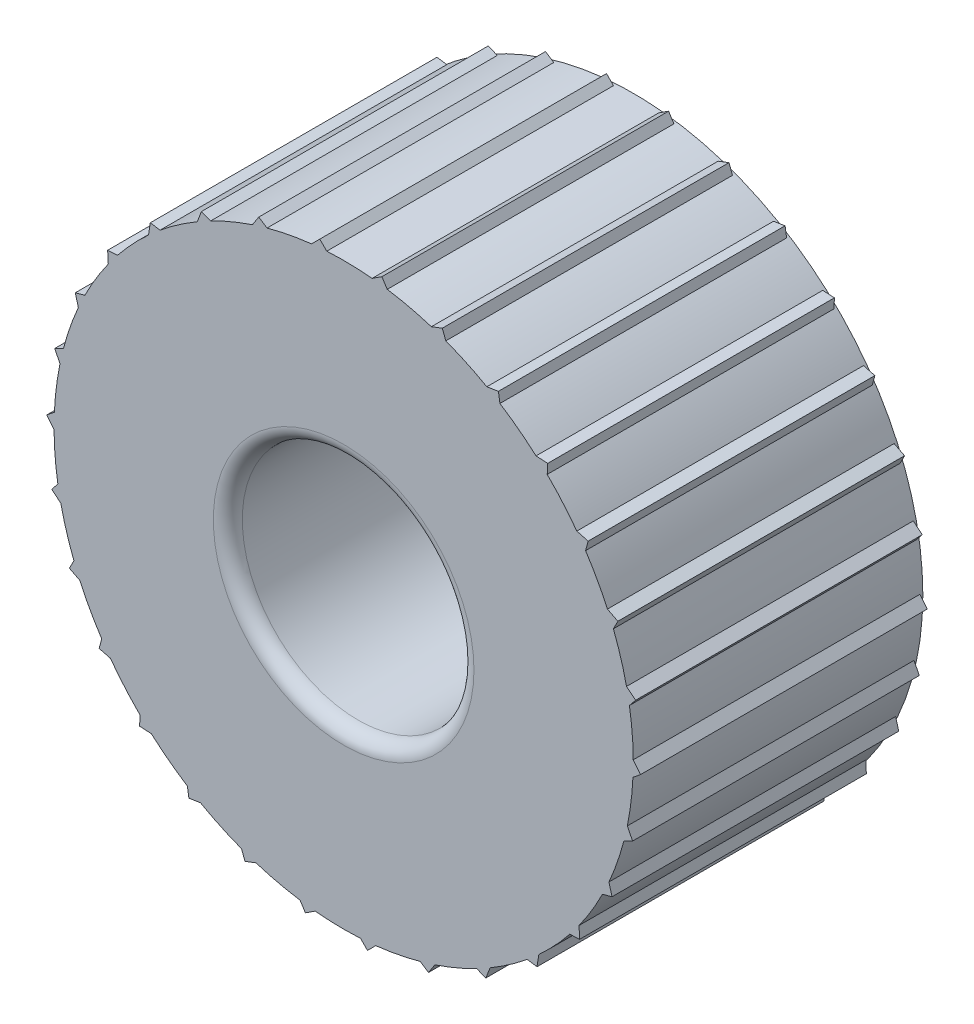
SolidWorks part; units mm, degrees
ref_plane "Front Plane" through (0, 0, 0) normal (0, 0, 1) x (1, 0, 0)
ref_plane "Top Plane" through (0, 0, 0) normal (0, 1, 0) x (1, 0, 0)
ref_plane "Right Plane" through (0, 0, 0) normal (1, 0, 0) x (0, 0, -1)
sketch "Sketch2" plane through (0, 0, 0) normal (0, 0, 1) x (1, 0, 0)
  circle A0 centre (0, 0) radius 100
  circle A1 centre (0, 0) radius 40
  circle A2 centre (0, 0) radius 50
  dimension "D1" = 200
  dimension "D2" = 80
  dimension "D3" = 100
extrude "Boss-Extrude2" add sketch "Sketch2" against normal blind 100 contours A0 A2
sketch "Sketch3" plane through (0, 0, 0) normal (0, 0, 1) x (1, 0, 0)
  circle A0 centre (0, 0) radius 50
extrude "Boss-Extrude3" add sketch "Sketch3" against normal blind 100
sketch "Sketch4" plane through (0, 0, 0) normal (0, 0, 1) x (1, 0, 0)
  circle A0 centre (0, 0) radius 40
  dimension "D1" = 80
extrude "Cut-Extrude1" cut sketch "Sketch4" against normal blind 100
fillet "Fillet1" radius 5 1 edges at (40, 0, 0)
fillet "Fillet2" radius 5 1 edges at (40, 0, -100)
sketch "Sketch9" plane through (0, 0, 0) normal (0, 0, 1) x (1, 0, 0)
  line L0 (-11.0942, 99.3827) -> (-8.237, 102.2399)
  line L1 (-8.237, 102.2399) -> (-5.8271, 99.8301)
  line L2 (13.1999, 101.7183) -> (15.056, 98.8601)
  line L3 (9.8111, 99.5176) -> (13.1999, 101.7183)
  line L4 (34.0599, 96.7511) -> (35.2812, 93.5694)
  line L5 (30.2875, 95.303) -> (34.0599, 96.7511)
  line L6 (53.4313, 87.5554) -> (53.9644, 84.1893)
  line L7 (49.4403, 86.9233) -> (53.4313, 87.5554)
  line L8 (70.4674, 74.5331) -> (70.2891, 71.1298)
  line L9 (66.4323, 74.7446) -> (70.4674, 74.5331)
  line L10 (84.4239, 58.2534) -> (83.5418, 54.9615)
  line L11 (80.5208, 59.2992) -> (84.4239, 58.2534)
  line L12 (94.6906, 39.4277) -> (93.1434, 36.3911)
  line L13 (91.0903, 41.2621) -> (94.6906, 39.4277)
  line L14 (100.8188, 18.8788) -> (98.6741, 16.2303)
  line L15 (97.6786, 21.4217) -> (100.8188, 18.8788)
  line L16 (102.5408, -2.4951) -> (99.8923, -4.6399)
  line L17 (99.9979, 0.6451) -> (102.5408, -2.4951)
  line L18 (99.7813, -23.76) -> (96.7447, -25.3072)
  line L19 (97.9468, -20.1597) -> (99.7813, -23.76)
  line L20 (92.6608, -43.9865) -> (89.369, -44.8686)
  line L21 (91.615, -40.0835) -> (92.6608, -43.9865)
  line L22 (81.4907, -62.2906) -> (78.0873, -62.4689)
  line L23 (81.2792, -58.2554) -> (81.4907, -62.2906)
  line L24 (66.759, -77.8723) -> (63.3929, -77.3391)
  line L25 (67.3911, -73.8813) -> (66.759, -77.8723)
  line L26 (49.1096, -90.0505) -> (45.9279, -88.8292)
  line L27 (50.5576, -86.2782) -> (49.1096, -90.0505)
  line L28 (29.3138, -98.2932) -> (26.4556, -96.437)
  line L29 (31.5146, -94.9043) -> (29.3138, -98.2932)
  line L30 (8.237, -102.2399) -> (5.8271, -99.8301)
  line L31 (11.0942, -99.3827) -> (8.237, -102.2399)
  line L32 (-13.1999, -101.7183) -> (-15.056, -98.8601)
  line L33 (-9.8111, -99.5176) -> (-13.1999, -101.7183)
  line L34 (-34.0599, -96.7511) -> (-35.2812, -93.5694)
  line L35 (-30.2875, -95.303) -> (-34.0599, -96.7511)
  line L36 (-53.4313, -87.5554) -> (-53.9644, -84.1893)
  line L37 (-49.4403, -86.9233) -> (-53.4313, -87.5554)
  line L38 (-70.4674, -74.5331) -> (-70.2891, -71.1298)
  line L39 (-66.4323, -74.7446) -> (-70.4674, -74.5331)
  line L40 (-84.4239, -58.2534) -> (-83.5418, -54.9615)
  line L41 (-80.5208, -59.2992) -> (-84.4239, -58.2534)
  line L42 (-94.6906, -39.4277) -> (-93.1434, -36.3911)
  line L43 (-91.0903, -41.2621) -> (-94.6906, -39.4277)
  line L44 (-100.8188, -18.8788) -> (-98.6741, -16.2303)
  line L45 (-97.6786, -21.4217) -> (-100.8188, -18.8788)
  line L46 (-102.5408, 2.4951) -> (-99.8923, 4.6399)
  line L47 (-99.9979, -0.6451) -> (-102.5408, 2.4951)
  line L48 (-99.7813, 23.76) -> (-96.7447, 25.3072)
  line L49 (-97.9468, 20.1597) -> (-99.7813, 23.76)
  line L50 (-92.6608, 43.9865) -> (-89.369, 44.8686)
  line L51 (-91.615, 40.0835) -> (-92.6608, 43.9865)
  line L52 (-81.4907, 62.2906) -> (-78.0873, 62.4689)
  line L53 (-81.2792, 58.2554) -> (-81.4907, 62.2906)
  line L54 (-66.759, 77.8723) -> (-63.3929, 77.3391)
  line L55 (-67.3911, 73.8813) -> (-66.759, 77.8723)
  line L56 (-49.1096, 90.0505) -> (-45.9279, 88.8292)
  line L57 (-50.5576, 86.2782) -> (-49.1096, 90.0505)
  line L58 (-29.3138, 98.2932) -> (-26.4556, 96.437)
  line L59 (-31.5146, 94.9043) -> (-29.3138, 98.2932)
  circle A0 centre (0, 0) radius 100 construction
  arc A1 (-11.0942, 99.3827) -> (-5.8271, 99.8301) centre (0, 0) cw
  arc A2 (9.8111, 99.5176) -> (15.056, 98.8601) centre (0, 0) cw
  arc A3 (30.2875, 95.303) -> (35.2812, 93.5694) centre (0, 0) cw
  arc A4 (49.4403, 86.9233) -> (53.9644, 84.1893) centre (0, 0) cw
  arc A5 (66.4323, 74.7446) -> (70.2891, 71.1298) centre (0, 0) cw
  arc A6 (80.5208, 59.2992) -> (83.5418, 54.9615) centre (0, 0) cw
  arc A7 (91.0903, 41.2621) -> (93.1434, 36.3911) centre (0, 0) cw
  arc A8 (97.6786, 21.4217) -> (98.6741, 16.2303) centre (0, 0) cw
  arc A9 (99.9979, 0.6451) -> (99.8923, -4.6399) centre (0, 0) cw
  arc A10 (97.9468, -20.1597) -> (96.7447, -25.3072) centre (0, 0) cw
  arc A11 (91.615, -40.0835) -> (89.369, -44.8686) centre (0, 0) cw
  arc A12 (81.2792, -58.2554) -> (78.0873, -62.4689) centre (0, 0) cw
  arc A13 (67.3911, -73.8813) -> (63.3929, -77.3391) centre (0, 0) cw
  arc A14 (50.5576, -86.2782) -> (45.9279, -88.8292) centre (0, 0) cw
  arc A15 (31.5146, -94.9043) -> (26.4556, -96.437) centre (0, 0) cw
  arc A16 (11.0942, -99.3827) -> (5.8271, -99.8301) centre (0, 0) cw
  arc A17 (-9.8111, -99.5176) -> (-15.056, -98.8601) centre (0, 0) cw
  arc A18 (-30.2875, -95.303) -> (-35.2812, -93.5694) centre (0, 0) cw
  arc A19 (-49.4403, -86.9233) -> (-53.9644, -84.1893) centre (0, 0) cw
  arc A20 (-66.4323, -74.7446) -> (-70.2891, -71.1298) centre (0, 0) cw
  arc A21 (-80.5208, -59.2992) -> (-83.5418, -54.9615) centre (0, 0) cw
  arc A22 (-91.0903, -41.2621) -> (-93.1434, -36.3911) centre (0, 0) cw
  arc A23 (-97.6786, -21.4217) -> (-98.6741, -16.2303) centre (0, 0) cw
  arc A24 (-99.9979, -0.6451) -> (-99.8923, 4.6399) centre (0, 0) cw
  arc A25 (-97.9468, 20.1597) -> (-96.7447, 25.3072) centre (0, 0) cw
  arc A26 (-91.615, 40.0835) -> (-89.369, 44.8686) centre (0, 0) cw
  arc A27 (-81.2792, 58.2554) -> (-78.0873, 62.4689) centre (0, 0) cw
  arc A28 (-67.3911, 73.8813) -> (-63.3929, 77.3391) centre (0, 0) cw
  arc A29 (-50.5576, 86.2782) -> (-45.9279, 88.8292) centre (0, 0) cw
  arc A30 (-31.5146, 94.9043) -> (-26.4556, 96.437) centre (0, 0) cw
  dimension "D1" = 30
extrude "Boss-Extrude4" add sketch "Sketch9" against normal blind 99
